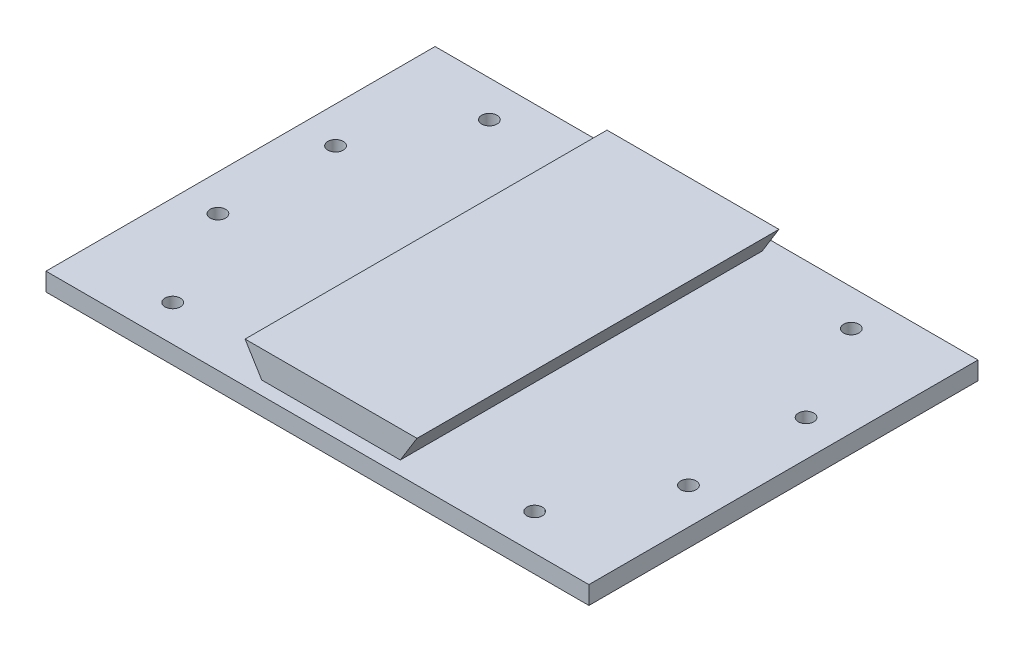
SolidWorks part; units mm, degrees
ref_plane "Front Plane" through (0, 0, 0) normal (0, 0, 1) x (1, 0, 0)
ref_plane "Top Plane" through (0, 0, 0) normal (0, 1, 0) x (1, 0, 0)
ref_plane "Right Plane" through (0, 0, 0) normal (1, 0, 0) x (0, 0, -1)
sketch "Sketch1" plane through (0, 0, 0) normal (0, 1, 0) x (1, 0, 0)
  line L1 (-60, -43) -> (60, -43)
  line L2 (-60, -43) -> (-60, 43)
  line L3 (-60, 43) -> (60, 43)
  line L4 (60, -43) -> (60, 43)
extrude "Rail Plate" add sketch "Sketch1" along normal blind 4
sketch "Sketch2" plane through (0, 0, 0) normal (0, 0, 1) x (1, 0, 0)
  line L0 (-15, 3.5) -> (15, 3.5)
  line L1 (15, 3.5) -> (19, 10)
  line L2 (19, 10) -> (-19, 10)
  line L3 (-19, 10) -> (-15, 3.5)
extrude "Dovetail Rail" add sketch "Sketch2" along normal mid plane 80
sketch "Sketch3" plane through (0, 0, 0) normal (0, 1, 0) x (1, 0, 0)
  circle A0 centre (-40, -35) radius 1.7
  circle A1 centre (-40, 35) radius 1.7
  circle A2 centre (40, -35) radius 1.7
  circle A3 centre (40, 35) radius 1.7
  circle A4 centre (-52, -13) radius 1.7
  circle A5 centre (-52, 13) radius 1.7
  circle A6 centre (52, -13) radius 1.7
  circle A7 centre (52, 13) radius 1.7
extrude "Bolt Holes" cut sketch "Sketch3" against normal through all and the other way through all
equation "\"PlateW\" = 120.0"
equation "\"PlateH\" = 86.0"
equation "\"PlateT\" = 4.0"
equation "\"RailW\" = 30.0"
equation "\"RailW2\" = 38.0"
equation "\"RailH\" = 6.0"
equation "\"RailL\" = 80.0"
equation "\"JoinL\" = 44.0"
equation "\"JoinW\" = 20.0"
equation "\"JoinT\" = 3.0"
equation "\"JoinPitch\" = 24.0"
equation "\"BoltD\" = 3.4"
